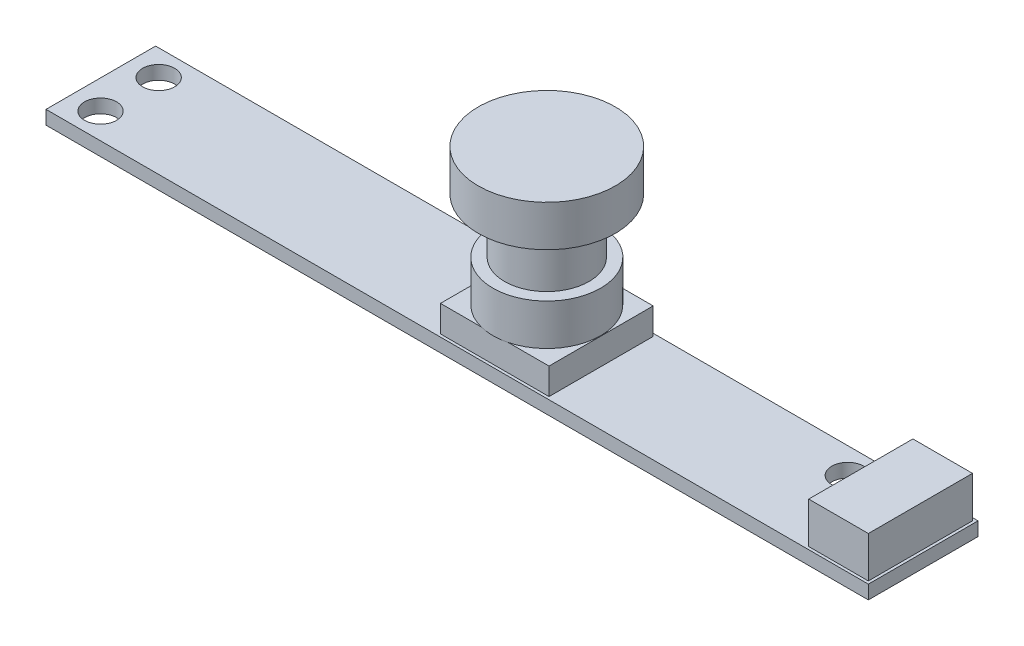
SolidWorks part; units mm, degrees
ref_plane "Front Plane" through (0, 0, 0) normal (0, 0, 1) x (1, 0, 0)
ref_plane "Top Plane" through (0, 0, 0) normal (0, 1, 0) x (1, 0, 0)
ref_plane "Right Plane" through (0, 0, 0) normal (1, 0, 0) x (0, 0, -1)
sketch "Sketch1" plane through (0, 0, 0) normal (0, 1, 0) x (1, 0, 0)
  line L1 (0, 0) -> (60, 0)
  line L2 (0, 0) -> (0, -8)
  line L3 (0, -8) -> (60, -8)
  line L4 (60, 0) -> (60, -8)
  dimension "D1" = 8
  dimension "D2" = 60
extrude "Boss-Extrude1" add sketch "Sketch1" along normal blind 1
sketch "Sketch2" plane through (0, 1, 0) normal (0, 1, 0) x (1, 0, 0)
  line L0 (60, -8) -> (60, 0) construction
  line L1 (59.8, -7.8) -> (55.45, -7.8)
  line L2 (59.8, -7.8) -> (59.8, -0.2)
  line L3 (59.8, -0.2) -> (55.45, -0.2)
  line L4 (55.45, -7.8) -> (55.45, -0.2)
  line L5 (0, -8) -> (60, -8) construction
  line L6 (60, 0) -> (0, 0) construction
  dimension "D1" = 4.35
  dimension "D2" = 0.2
  dimension "D3" = 0.2
  dimension "D4" = 0.2
extrude "Boss-Extrude2" add sketch "Sketch2" along normal blind 3
sketch "Sketch3" plane through (0, 1, 0) normal (0, 1, 0) x (1, 0, 0)
  line L0 (60, -8) -> (60, 0) construction
  line L1 (60, 0) -> (0, 0) construction
  line L2 (0, 0) -> (0, -8) construction
  line L3 (0, -8) -> (60, -8) construction
  circle A0 centre (52.38, -1.88) radius 1.17
  circle A1 centre (2.1, -6.12) radius 1.17
  circle A2 centre (2.1, -1.88) radius 1.17
  dimension "D3" = 2.34
  dimension "D8" = 2.34
  dimension "D9" = 2.34
  dimension "D1" = 7.62
  dimension "D2" = 1.88
  dimension "D4" = 2.1
  dimension "D5" = 2.1
  dimension "D6" = 1.88
  dimension "D7" = 1.88
extrude "Cut-Extrude1" cut sketch "Sketch3" against normal blind 3
sketch "Sketch4" plane through (0, 1, 0) normal (0, 1, 0) x (1, 0, 0)
  line L0 (60, 0) -> (0, 0) construction
  line L1 (28.58, -7.8) -> (36.5, -7.8)
  line L2 (28.58, -7.8) -> (28.58, -0.2)
  line L3 (28.58, -0.2) -> (36.5, -0.2)
  line L4 (36.5, -7.8) -> (36.5, -0.2)
  line L5 (0, -8) -> (60, -8) construction
  line L6 (60, -8) -> (60, 0) construction
  dimension "D1" = 0.2
  dimension "D2" = 0.2
  dimension "D3" = 23.5
  dimension "D4" = 7.92
extrude "Boss-Extrude3" add sketch "Sketch4" along normal blind 1.93
sketch "Sketch5" plane through (0, 2.93, 0) normal (0, 1, 0) x (1, 0, 0)
  circle A0 centre (32.54, -4) radius 3.925
  dimension "D1" = 7.85
extrude "Boss-Extrude4" add sketch "Sketch5" along normal blind 3
sketch "Sketch6" plane through (0, 5.93, 0) normal (0, 1, 0) x (1, 0, 0)
  circle A0 centre (32.54, -4) radius 3.08
  dimension "D1" = 6.16
extrude "Boss-Extrude5" add sketch "Sketch6" along normal blind 4
sketch "Sketch7" plane through (0, 9.93, 0) normal (0, 1, 0) x (1, 0, 0)
  circle A0 centre (32.54, -4) radius 5
  dimension "D1" = 10
extrude "Boss-Extrude6" add sketch "Sketch7" along normal blind 3
equation "\"D8@Sketch3\"=\"D3@Sketch3\""
equation "\"D9@Sketch3\"=\"D3@Sketch3\""
